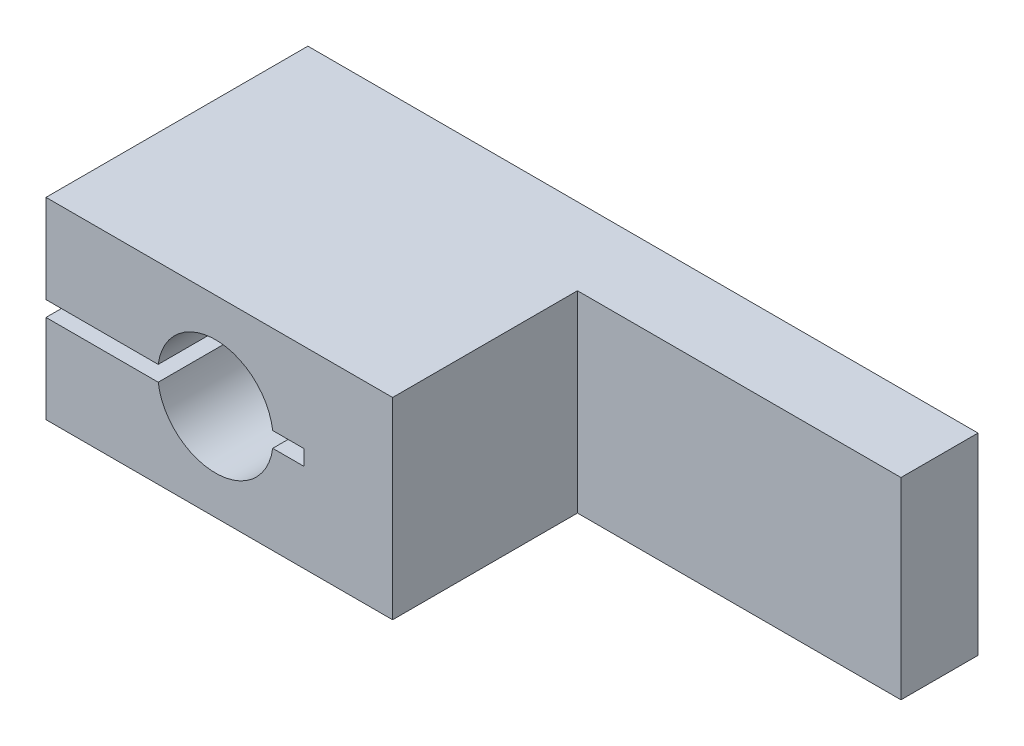
SolidWorks part; units mm, degrees
material "1.4301 (X5CrNi18-10)"
ref_plane "Vorne" through (0, 0, 0) normal (0, 0, 1) x (1, 0, 0)
ref_plane "Oben" through (0, 0, 0) normal (0, 1, 0) x (1, 0, 0)
ref_plane "Rechts" through (0, 0, 0) normal (1, 0, 0) x (0, 0, -1)
sketch "Skizze1" plane through (0, 0, 0) normal (0, 0, 1) x (1, 0, 0)
  line L0 (-22, -1) -> (-22, -12.5)
  line L1 (11.5, 0) -> (0, 0) construction
  line L2 (7.433, 1) -> (11.5, 1)
  line L3 (-22, -12.5) -> (65, -12.5)
  line L4 (65, 12.5) -> (65, -12.5)
  line L6 (-22, 12.5) -> (-22, 1)
  line L7 (7.433, -1) -> (11.5, -1)
  line L8 (65, 12.5) -> (-22, 12.5)
  line L9 (-22, 1) -> (-7.433, 1)
  line L10 (11.5, 1) -> (11.5, -1)
  line L11 (-22, -1) -> (-7.433, -1)
  arc A0 (-7.433, -1) -> (7.433, -1) centre (0, 0) ccw
  arc A1 (7.433, 1) -> (-7.433, 1) centre (0, 0) ccw
  dimension "D1" = 15
  dimension "D2" = 2
  dimension "D3" = 1
  dimension "D4" = 11.5
  dimension "D5" = 25
  dimension "D6" = 12.5
  dimension "D7" = 22
  dimension "D9" = 65
extrude "Linear austragen1" add sketch "Skizze1" against normal blind 34
sketch "Skizze8" plane through (0, -12.5, 0) normal (0, -1, 0) x (1, 0, 0)
  line L1 (65, 0) -> (23, 0)
  line L2 (65, 0) -> (65, -24)
  line L3 (65, -24) -> (23, -24)
  line L4 (23, 0) -> (23, -24)
  line L5 (65, -34) -> (65, 0) construction
  line L6 (-22, 0) -> (65, 0) construction
  line L7 (-22, -34) -> (65, -34) construction
  dimension "D1" = 10
  dimension "D3" = 42
extrude "Schnitt-Linear austragen1" cut sketch "Skizze8" against normal up to next
hole_wizard "Durchgangsloch für M61" [suppressed] positions "Skizze5" profile "Skizze4" hole size "M6" standard "Gabler-Normteile"
sketch "Skizze5" plane through (0, -12.5, 0) normal (0, 1, 0) x (-1, 0, 0)
  line L0 (22, -34) -> (22, 0) construction
  line L1 (-23, 0) -> (22, 0) construction
  point P0 (14, -8)
  point P5 (14, -26)
  dimension "D1" = 8
  dimension "D2" = 8
  dimension "D3" = 18
sketch "Skizze4" plane through (-14, -12.5, -8) normal (1, 0, 0) x (0, 0, -1)
  line L0 (0, 0) -> (0, 14.9828)
  line L1 (0, 14.9828) -> (3.3, 13)
  line L2 (3.3, 13) -> (3.3, 0)
  line L5 (3.3, 0) -> (0, 0)
  line L10 (0, 14.9828) -> (-3.3, 13) construction
  line L11 (0, -6.35) -> (0, 107.95) construction
  dimension "Bohrerdurchmesser" = 6.6
  dimension "Bohrungstiefe" = 13
  dimension "Spitzenwinkel" = 118
hole_wizard "M6 Gewindebohrung1" [suppressed] positions "Skizze7" profile "Skizze6" tap size "M6" standard "Gabler-Normteile"
sketch "Skizze7" [suppressed] plane through (0, 12.5, 0) normal (0, 1, 0) x (-1, 0, 0)
  line L0 (22, -34) -> (22, 0) construction
  line L1 (-23, 0) -> (22, 0) construction
  point P0 (14, -8)
  point P8 (14, -26)
  dimension "D1" = 8
  dimension "D2" = 8
sketch "Skizze6" plane through (-14, 12.5, -8) normal (1, 0, 0) x (0, 0, 1)
  line L0 (0, 0) -> (0, 25)
  line L1 (0, 25) -> (2.5, 25)
  line L2 (2.5, 25) -> (2.5, 0)
  line L5 (2.5, 0) -> (0, 0)
  line L11 (0, -6.35) -> (0, 107.95) construction
  dimension "Bohrerdurchmesser" = 5
  dimension "Bohrungstiefe" = 25
cosmetic thread "Bohrungsgewinde6" [suppressed] parameters "D1"=11.5, "D2"=6
cosmetic thread "Bohrungsgewinde7" [suppressed] parameters "D1"=11.5, "D2"=6
hole_wizard "M10 Gewindebohrung1" [suppressed] positions "Skizze10" profile "Skizze9" tap size "M10" standard "Gabler-Normteile"
sketch "Skizze10" plane through (0, 0, -34) normal (0, 0, -1) x (-1, 0, 0)
  line L1 (-65, -12.5) -> (-65, 12.5) construction
  point P0 (-51, 0)
  dimension "D2" = 14
cosmetic thread "Bohrungsgewinde3" [suppressed] parameters "D2"=10
sketch "Skizze9" plane through (51, 0, -34) normal (1, 0, 0) x (0, 1, 0)
  line L0 (0, 0) -> (0, 34)
  line L1 (0, 34) -> (4.25, 34)
  line L2 (4.25, 34) -> (4.25, 0)
  line L5 (4.25, 0) -> (0, 0)
  line L11 (0, -6.35) -> (0, 107.95) construction
  dimension "Bohrerdurchmesser" = 8.5
  dimension "Bohrungstiefe" = 34
